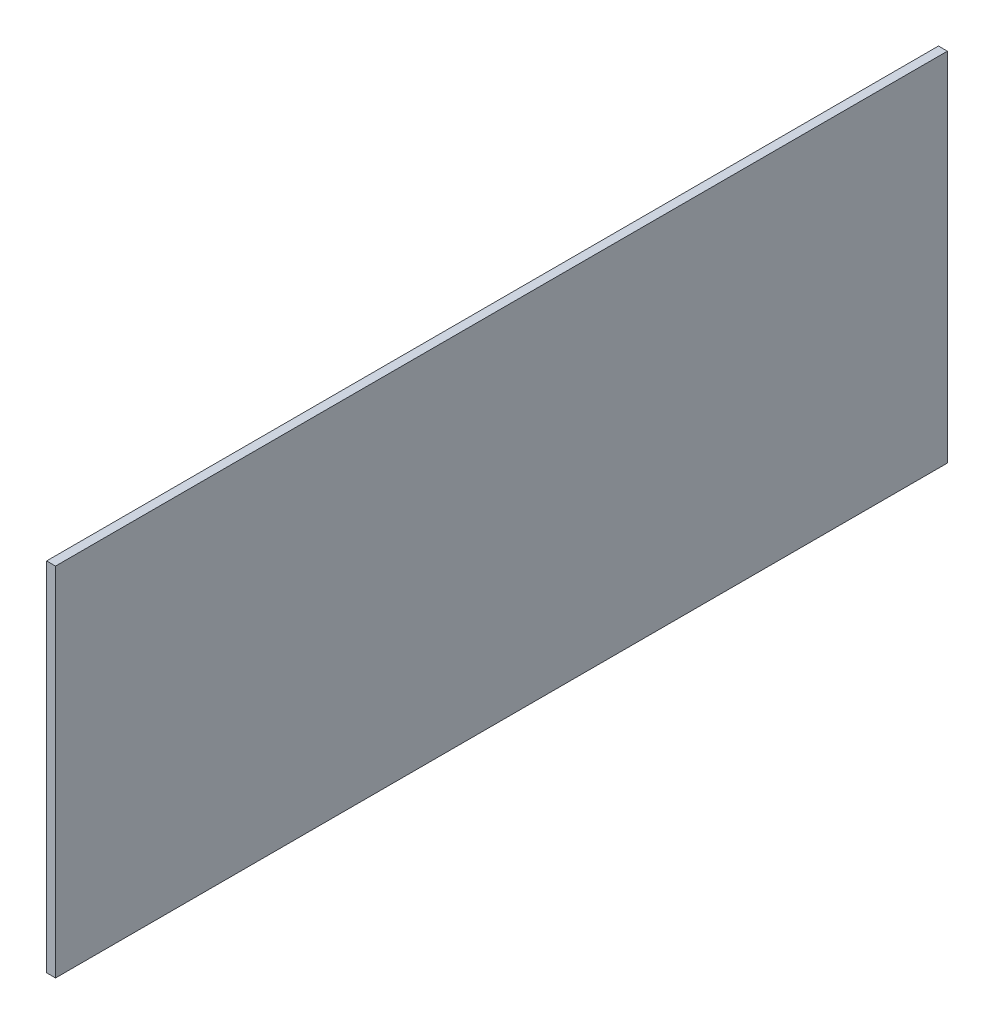
SolidWorks part; units mm, degrees
ref_plane "Front Plane" through (0, 0, 0) normal (0, 0, 1) x (1, 0, 0)
ref_plane "Top Plane" through (0, 0, 0) normal (0, 1, 0) x (1, 0, 0)
ref_plane "Right Plane" through (0, 0, 0) normal (1, 0, 0) x (0, 0, -1)
sketch "Sketch1" plane through (0, 0, 0) normal (1, 0, 0) x (0, 0, -1)
  line L1 (500, -200) -> (-500, -200)
  line L2 (500, -200) -> (500, 200)
  line L3 (500, 200) -> (-500, 200)
  line L4 (-500, -200) -> (-500, 200)
  line L5 (500, -200) -> (-500, 200) construction
  line L6 (500, 200) -> (-500, -200) construction
  point P0 (0, 0)
extrude "Boss-Extrude1" add sketch "Sketch1" along normal blind 10
